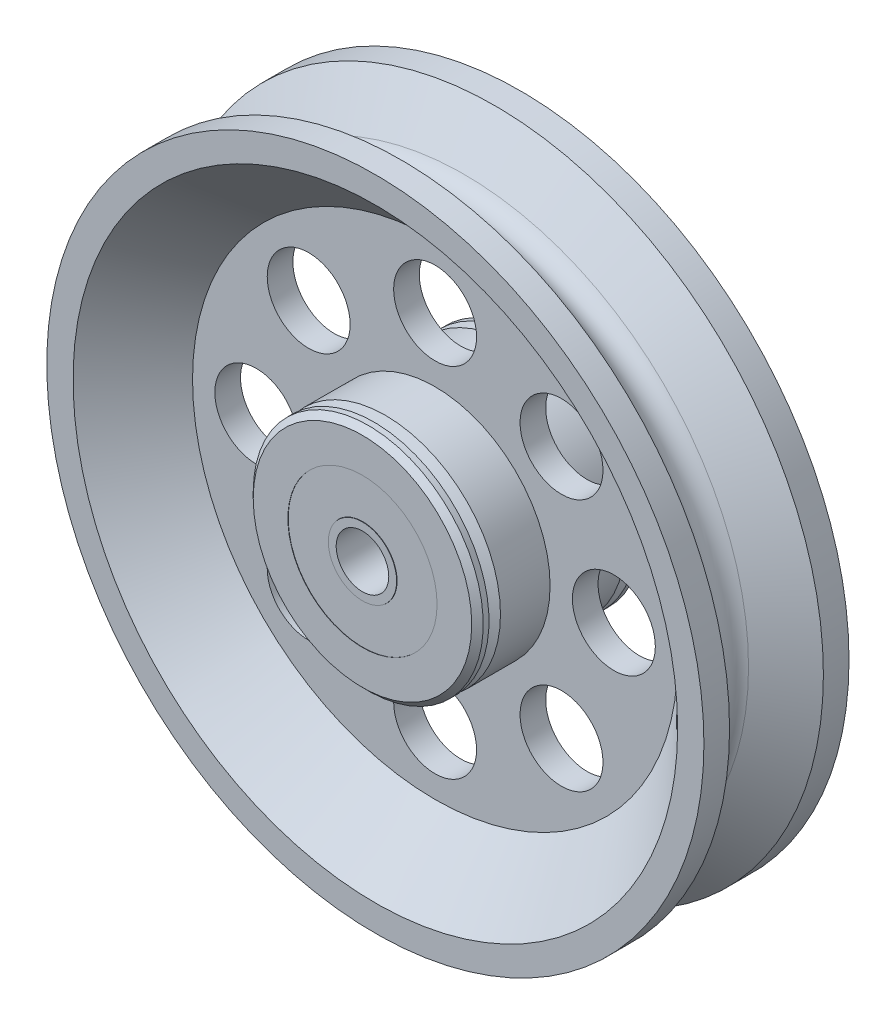
SolidWorks part; units mm, degrees
ref_plane "Front" through (0, 0, 0) normal (0, 0, 1) x (1, 0, 0)
ref_plane "Top" through (0, 0, 0) normal (0, 1, 0) x (1, 0, 0)
ref_plane "Right" through (0, 0, 0) normal (1, 0, 0) x (0, 0, -1)
sketch "Sketch1" plane through (0, 0, 0) normal (1, 0, 0) x (0, 0, -1)
  line L0 (11.3347, 79.375) -> (17.526, 79.375)
  line L1 (-11.3347, 79.375) -> (-17.526, 79.375)
  line L2 (-11.3347, 79.375) -> (-3.9076, 68.715)
  line L3 (20.5613, 18.0181) -> (20.5613, 8.255)
  line L4 (20.6375, 6.35) -> (-20.6375, 6.35)
  line L5 (-20.5613, 8.255) -> (-20.5613, 18.0181)
  line L6 (11.3347, 79.375) -> (3.9076, 68.715)
  line L8 (-20.6375, 0) -> (20.6375, 0) construction
  line L10 (17.526, 79.375) -> (17.526, 73.025)
  line L12 (-20.5613, 8.255) -> (-20.6375, 8.255)
  line L13 (-20.6375, 8.255) -> (-20.6375, 6.35)
  line L14 (0, 66.675) -> (0, -66.675) construction
  line L15 (20.6375, 8.255) -> (20.5613, 8.255)
  line L16 (20.6375, 8.255) -> (20.6375, 6.35)
  line L17 (-17.526, 79.375) -> (-17.526, -79.375) construction
  line L18 (-17.526, 73.025) -> (-3.0956, 58.5946)
  line L19 (-3.0956, 58.5946) -> (-3.0956, 27.7812)
  line L20 (-3.0956, 27.7812) -> (-20.6375, 27.7812)
  line L21 (-17.526, 73.025) -> (-17.526, 79.375)
  line L22 (17.526, 73.025) -> (3.0956, 58.5946)
  line L23 (3.0956, 58.5946) -> (3.0956, 27.7812)
  line L24 (3.0956, 27.7812) -> (20.6375, 27.7812)
  line L26 (-20.5613, 18.0181) -> (-20.6375, 18.0181)
  line L27 (-20.6375, 18.0181) -> (-20.6375, 27.7812)
  line L28 (20.6375, 27.7812) -> (20.6375, 18.0181)
  line L29 (20.6375, 18.0181) -> (20.5613, 18.0181)
  arc A0 (-3.9076, 68.715) -> (3.9076, 68.715) centre (0, 71.4375) ccw
  circle A1 centre (0, 71.4375) radius 4.7625 construction
  circle A2 centre (0, 0) radius 6.35 construction
  circle A3 centre (0, 0) radius 8.255 construction
  circle A4 centre (0, 0) radius 27.7813 construction
  circle A5 centre (0, -71.4375) radius 4.7625 construction
  point P28 (-17.526, 0)
  dimension "Rope Dia" = 9.525
  dimension "Shaft Dia" = 12.7
  dimension "D1" = 16.51
  dimension "D3" = 55.5625
  dimension "Wd" = 41.275
  dimension "D8" = 6.1913
  dimension "Groove Dia" = 133.35
  dimension "OD" = 158.75
  dimension "D6" = 0.0762
  dimension "D2" = 6.1913
  dimension "D4" = 45
  dimension "D5" = 6.35
  dimension "w Wd" = 35.052
  dimension "D7" = 30.8134
revolve "Revolve1" add sketch "Sketch1" angle 360 about L8
sketch "Sketch2" plane through (0, 0, 0) normal (0, 0, 1) x (1, 0, 0)
  circle A0 centre (0, 0) radius 8.255 construction
  circle A1 centre (0, 0) radius 8.255
extrude "Cut-Extrude-Thin1" cut sketch "Sketch2" against normal through all and the other way through all thin
chamfer "Chamfer1" distance 1.3891 angle 45 2 edges at (27.7812, 0, -20.6375) (27.7812, 0, 20.6375)
sketch "Sketch3" plane through (0, 0, 0) normal (1, 0, 0) x (0, 0, -1)
  line L0 (-17.8594, 27.7812) -> (-16.4703, 25.3753)
  line L1 (-3.0956, 27.7812) -> (-20.6375, 27.7812) construction
  line L2 (-16.4703, 25.3753) -> (-15.0813, 27.7812)
  line L5 (-20.6375, 27.7812) -> (-17.8594, 27.7812) construction
  line L6 (-17.8594, 27.7812) -> (-15.0813, 27.7812)
  point P6 (-19.2484, 27.7812)
  dimension "D1" = 60
revolve "Cut-Revolve1" cut sketch "Sketch3" angle 360
mirror "Mirror1" about plane through (0, 0, 0) normal (0, 0, 1) of "Cut-Revolve1"
sketch "Sketch4" plane through (0, 0, 0) normal (0, 0, 1) x (1, 0, 0)
  line L1 (0, 58.5946) -> (0, 27.7812) construction
  circle A0 centre (0, 43.1879) radius 10.0143
  circle A1 centre (0, 0) radius 58.5946 construction
  dimension "D3" = 20.0287
  dimension "D2" = 30.8134
extrude "Cut-Extrude1" cut sketch "Sketch4" against normal through all and the other way through all
pattern_circular "CirPattern1" count 8 over 360 about axis through (0, 0, 0) along (0, 0, 1) of "Cut-Extrude1"
equation "\"D1@Sketch1\" = \"Shaft Dia@Sketch1\" * 1.3"
equation "\"D3@Sketch1\" = \"OD@Sketch1\" * .35"
equation "\"D8@Sketch1\" = \"Wd@Sketch1\" * .15"
equation "\"D2@Sketch1\" = \"D8@Sketch1\""
equation "\"D5@Sketch1\" = \"OD@Sketch1\" * .04"
equation "\"D1@Chamfer1\" = \"D3@Sketch1\" * .025"
equation "\"D3@Sketch4\" = \"D2@Sketch4\" * .65"
